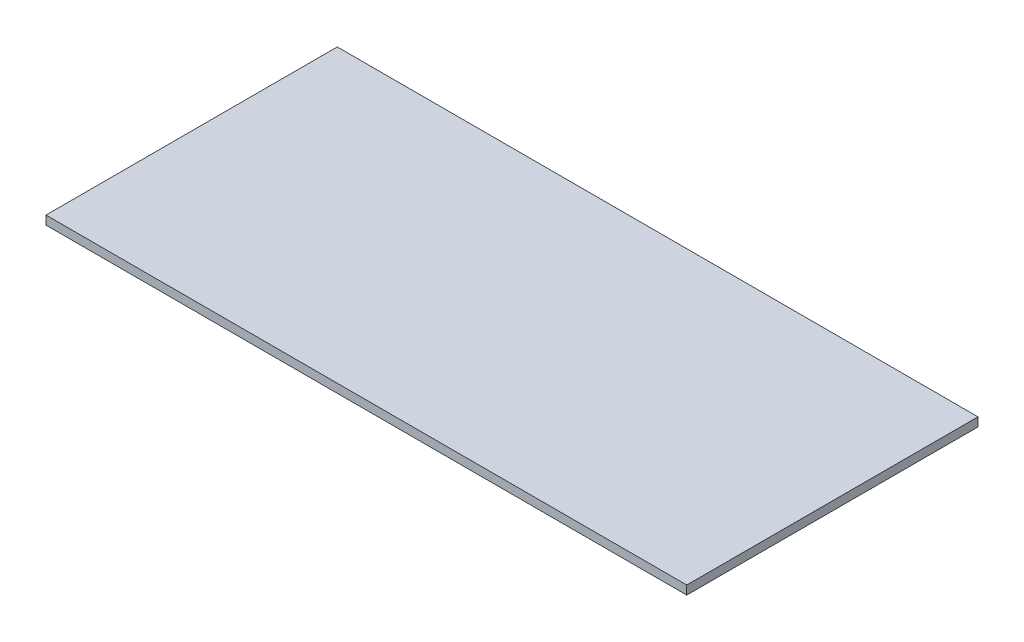
SolidWorks part; units mm, degrees
ref_plane "Front" through (0, 0, 0) normal (0, 0, 1) x (1, 0, 0)
ref_plane "Top" through (0, 0, 0) normal (0, 1, 0) x (1, 0, 0)
ref_plane "Right" through (0, 0, 0) normal (1, 0, 0) x (0, 0, -1)
sketch "Sketch1" plane through (0, 0, 0) normal (0, 1, 0) x (1, 0, 0)
  line L1 (0, 0) -> (220, 0)
  line L2 (0, 0) -> (0, 100)
  line L3 (0, 100) -> (220, 100)
  line L4 (220, 0) -> (220, 100)
  dimension "D1" = 220
  dimension "D2" = 100
extrude "Boss-Extrude1" add sketch "Sketch1" along normal blind 3
